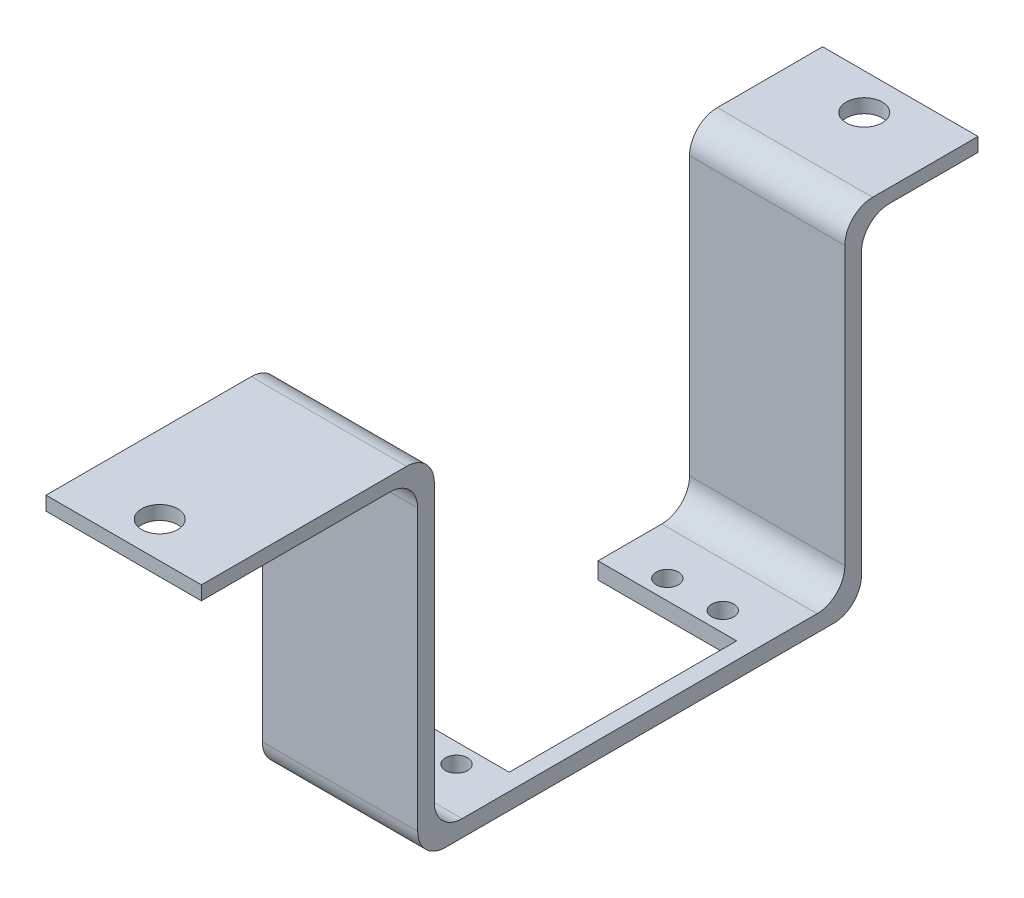
SolidWorks part; units mm, degrees
ref_plane "Front Plane" through (0, 0, 0) normal (0, 0, 1) x (1, 0, 0)
ref_plane "Top Plane" through (0, 0, 0) normal (0, 1, 0) x (1, 0, 0)
ref_plane "Right Plane" through (0, 0, 0) normal (1, 0, 0) x (0, 0, -1)
sketch "Sketch1" plane through (0, 0, 0) normal (0, 1, 0) x (1, 0, 0)
  line L1 (-16, 49) -> (16, 49)
  line L2 (-16, 49) -> (-16, -31)
  line L3 (-16, -31) -> (16, -31)
  line L4 (16, 49) -> (16, -31)
  dimension "D1" = 32
  dimension "D2" = 80
  dimension "D3" = 16
  dimension "D4" = 31
extrude "Boss-Extrude1" add sketch "Sketch1" along normal blind 3
sketch "Sketch4" plane through (0, 3, 0) normal (0, 1, 0) x (1, 0, 0)
  line L0 (-16, 49) -> (-16, -31) construction
  line L2 (-16, 49) -> (-16, -31)
  line L8 (16, 49) -> (16, -31)
  line L9 (16, -31) -> (16, 49) construction
  line L12 (-16, 49) -> (16, 49)
  line L15 (-13.5, 46) -> (13.5, 46)
  line L17 (-13.5, 46) -> (-13.5, -28)
  line L18 (13.5, 46) -> (13.5, -28)
  line L19 (13.5, -28) -> (-13.5, -28)
  line L20 (-16, -31) -> (16, -31)
  line L21 (16, 49) -> (-16, 49) construction
  line L22 (-16, -31) -> (16, -31) construction
  dimension "D1" = 3
  dimension "D2" = 2.5
  dimension "D3" = 3
  dimension "D4" = 2.5
extrude "Boss-Extrude2" add sketch "Sketch4" along normal blind 57.5
sketch "Sketch5" plane through (0, 60.5, 0) normal (0, 1, 0) x (1, 0, 0)
  line L1 (-16, 70) -> (16, 70)
  line L2 (-16, 70) -> (-16, -70)
  line L3 (-16, -70) -> (16, -70)
  line L4 (16, 70) -> (16, -70)
  dimension "D1" = 32
  dimension "D2" = 16
  dimension "D3" = 70
  dimension "D4" = 70
extrude "Boss-Extrude3" add sketch "Sketch5" along normal blind 2.5
sketch "Sketch2" plane through (0, 3, 0) normal (0, 1, 0) x (1, 0, 0)
  line L1 (-11, 29.5) -> (11, 29.5)
  line L2 (-11, 29.5) -> (-11, -11.5)
  line L3 (-11, -11.5) -> (11, -11.5)
  line L4 (11, 29.5) -> (11, -11.5)
  dimension "D4" = 41
  dimension "D5" = 11.5
  dimension "D6" = 22
  dimension "D7" = 11
extrude "Cut-Extrude1" cut sketch "Sketch2" against normal through all and the other way blind 50.8
sketch "Sketch6" plane through (0, 63, 0) normal (0, 1, 0) x (1, 0, 0)
  line L1 (-11, 46) -> (11, 46)
  line L2 (-11, 46) -> (-11, -28)
  line L3 (-11, -28) -> (11, -28)
  line L4 (11, 46) -> (11, -28)
  circle A2 centre (0, 63.5) radius 3.25
  circle A3 centre (0, -63.5) radius 3.25
  dimension "D1" = 22
  dimension "D4" = 6.5
  dimension "D2" = 11
  dimension "D3" = 74
  dimension "D5" = 63.5
  dimension "D6" = 63.5
  dimension "D7" = 28
extrude "Cut-Extrude2" cut sketch "Sketch6" against normal blind 25.4
sketch "Sketch7" plane through (0, 3, 0) normal (0, 1, 0) x (1, 0, 0)
  line L0 (-11, 29.5) -> (11, 29.5) construction
  line L1 (11, -11.5) -> (-11, -11.5) construction
  circle A0 centre (-5, 33) radius 2
  circle A1 centre (5, 33) radius 2
  circle A2 centre (-5, -15) radius 2
  circle A3 centre (5, -15) radius 2
  dimension "D5" = 4
  dimension "D1" = 3.5
  dimension "D2" = 3.5
  dimension "D3" = 10
  dimension "D4" = 5
sketch "Sketch8" plane through (16, 0, 0) normal (1, 0, 0) x (0, 0, -1)
  line L0 (-70, 63) -> (70, 63) construction
  line L1 (-28, 63) -> (46, 63)
  line L2 (-28, 63) -> (-28, 3)
  line L3 (-28, 3) -> (46, 3)
  line L4 (46, 63) -> (46, 3)
  line L5 (-31, 60.5) -> (-31, 0) construction
  line L6 (-31, 0) -> (49, 0) construction
  dimension "D1" = 74
  dimension "D2" = 3
  dimension "D3" = 3
extrude "Cut-Extrude3" cut sketch "Sketch8" against normal through all both and the other way through all
extrude "Cut-Extrude4" cut sketch "Sketch7" against normal through all
sketch "Sketch10" plane through (0, 63, 0) normal (0, 1, 0) x (1, 0, 0)
  line L0 (16, 70) -> (-16, 70) construction
  line L1 (-16, -70) -> (-14, -70)
  line L2 (-16, -70) -> (-16, 70)
  line L3 (-16, 70) -> (-14, 70)
  line L4 (-14, -70) -> (-14, 70)
  line L5 (-11, -11.5) -> (-11, 29.5) construction
  line L6 (11, 29.5) -> (11, -11.5) construction
  line L7 (16, -70) -> (14, -70)
  line L8 (16, -70) -> (16, 70)
  line L9 (16, 70) -> (14, 70)
  line L10 (14, -70) -> (14, 70)
  dimension "D1" = 3
  dimension "D2" = 3
extrude "Cut-Extrude5" cut sketch "Sketch10" against normal through all
fillet "Fillet1" radius 5 8 edges at (0, 3, -46) (0, 3, 28) (0, 0, 31) (0, 0, -49) (0, 60.5, 31) (0, 60.5, -49) (0, 63, -46) (0, 63, 28)
sketch "Sketch13" plane through (0, 3, 0) normal (0, 1, 0) x (1, 0, 0)
  line L0 (-14, -23) -> (-14, 41) construction
  line L1 (-11, -11.5) -> (-14, -11.5)
  line L2 (-11, -11.5) -> (-11, 29.5)
  line L3 (-11, 29.5) -> (-14, 29.5)
  line L4 (-14, -11.5) -> (-14, 29.5)
extrude "Cut-Extrude7" cut sketch "Sketch13" against normal through all
